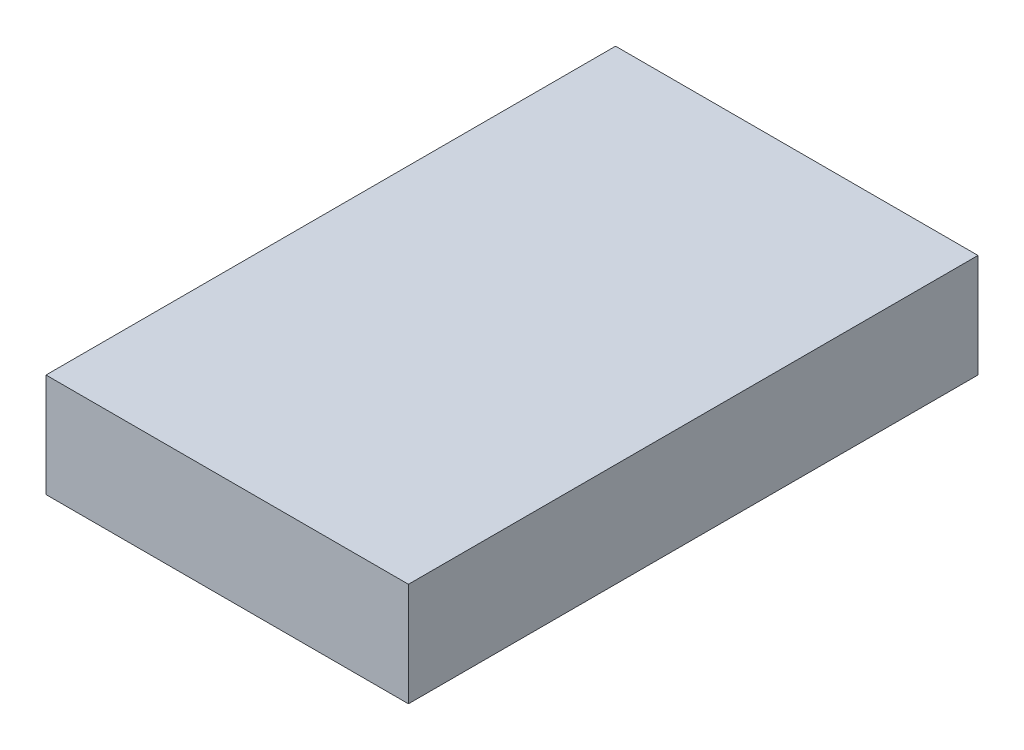
SolidWorks part; units mm, degrees
material "Oak"
ref_plane "Front Plane" through (0, 0, 0) normal (0, 0, 1) x (1, 0, 0)
ref_plane "Top Plane" through (0, 0, 0) normal (0, 1, 0) x (1, 0, 0)
ref_plane "Right Plane" through (0, 0, 0) normal (1, 0, 0) x (0, 0, -1)
sketch "Sketch1" plane through (0, 0, 0) normal (0, 1, 0) x (1, 0, 0)
  line L1 (-22.225, -34.925) -> (22.225, -34.925)
  line L2 (-22.225, -34.925) -> (-22.225, 34.925)
  line L3 (-22.225, 34.925) -> (22.225, 34.925)
  line L4 (22.225, -34.925) -> (22.225, 34.925)
  line L5 (-22.225, -34.925) -> (22.225, 34.925) construction
  line L6 (-22.225, 34.925) -> (22.225, -34.925) construction
  point P0 (0, 0)
  dimension "D1" = 44.45
  dimension "D2" = 69.85
extrude "Boss-Extrude1" add sketch "Sketch1" along normal mid plane 12.7
